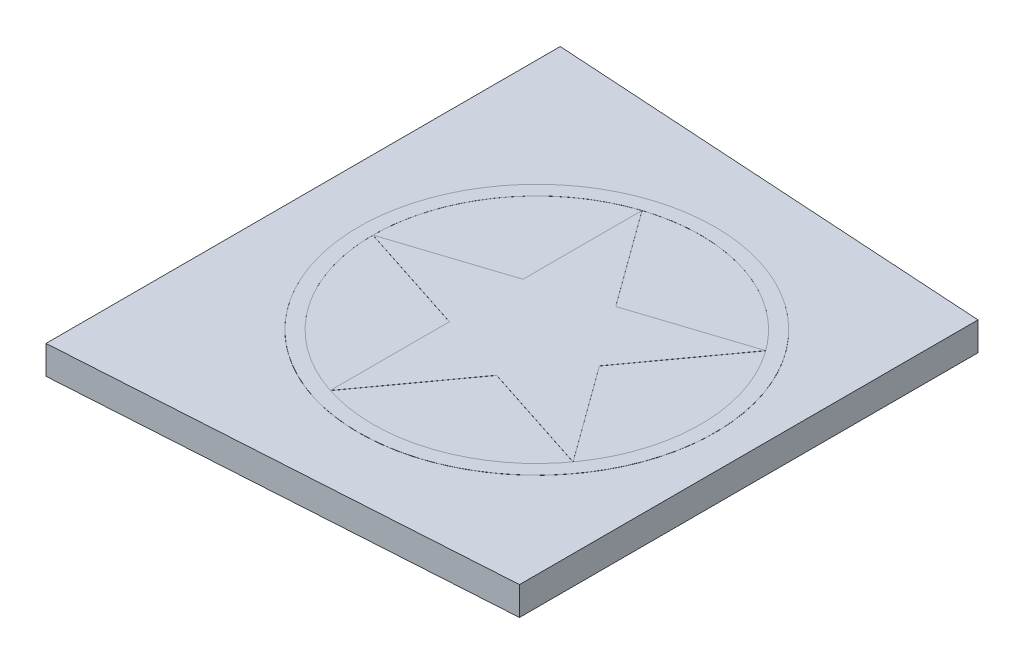
SolidWorks part; units mm, degrees
ref_plane "Front Plane" through (0, 0, 0) normal (0, 0, 1) x (1, 0, 0)
ref_plane "Top Plane" through (0, 0, 0) normal (0, 1, 0) x (1, 0, 0)
ref_plane "Right Plane" through (0, 0, 0) normal (1, 0, 0) x (0, 0, -1)
sketch "Sketch1" plane through (0, 0, 0) normal (0, 1, 0) x (1, 0, 0)
  line L0 (-180.913, 131.6179) -> (-180.913, -48.8021)
  line L1 (-180.913, 131.6179) -> (-24.573, 121.8366)
  line L2 (-180.913, -48.8021) -> (-24.573, -39.0208)
  line L3 (-24.573, 121.8366) -> (-24.573, -39.0208)
  dimension "D1" = 180.42
  dimension "D2" = 156.34
  dimension "D3" = 86.42
  dimension "D4" = 86.42
  dimension "D5" = 156.34
extrude "Boss-Extrude1" add sketch "Sketch1" along normal blind 10
sketch "Sketch3" plane through (7.4971, 0, -119.8301) normal (0.0624, 0, -0.998) x (-0.998, 0, -0.0624)
  line L0 (32.1327, 10) -> (188.7784, 10) construction
  line L1 (188.7784, 10) -> (188.7784, 0) construction
  circle A0 centre (181.7784, 4.88) radius 4.62
  dimension "D2" = 9.24
  dimension "D1" = 5.12
  dimension "D3" = 7
extrude "Cut-Extrude3" cut sketch "Sketch3" against normal blind 6
sketch "Sketch4" plane through (0, 10, 0) normal (0, 1, 0) x (1, 0, 0)
  line L0 (-180.913, 41.4079) -> (-24.573, 41.4079)
  line L1 (-52.4011, 75.2008) -> (-92.1368, 62.2899)
  line L2 (-92.1368, 62.2899) -> (-116.6914, 96.0936)
  line L3 (-180.913, 131.6179) -> (-180.913, -48.8021) construction
  line L4 (-24.573, -39.0208) -> (-24.573, 121.8366) construction
  line L5 (-116.6859, 96.0954) -> (-116.6859, 54.3148)
  line L6 (-116.6859, 54.3148) -> (-156.423, 41.4079)
  line L7 (-52.4079, 7.6055) -> (-76.9659, 41.4068)
  line L8 (-76.9659, 41.4068) -> (-52.4045, 75.2055)
  line L9 (-116.6969, -13.2761) -> (-92.1389, 20.5252)
  line L10 (-92.1389, 20.5252) -> (-52.4045, 7.6102)
  line L11 (-156.423, 41.4137) -> (-116.6872, 28.5027)
  line L12 (-116.6872, 28.5027) -> (-116.6914, -13.2779)
  circle A1 centre (-98.923, 41.4079) radius 62.5
  circle A2 centre (-98.923, 41.4079) radius 57.5
  point P27 (-98.923, 41.4079)
  line M1 (-24.573, 121.8366) -> (-180.913, 131.6179)
  dimension "D1" = 67.6
  dimension "D2" = 5
  dimension "D3" = 5
extrude "Boss-Extrude2" add sketch "Sketch4" along normal blind 0.05 contours L6 L11 L0 L8 L1 L2 L5 | L11 L12 L9 L10 L7 L8 L0 | A2 L0 A1 | A2 L0 A1 M1
